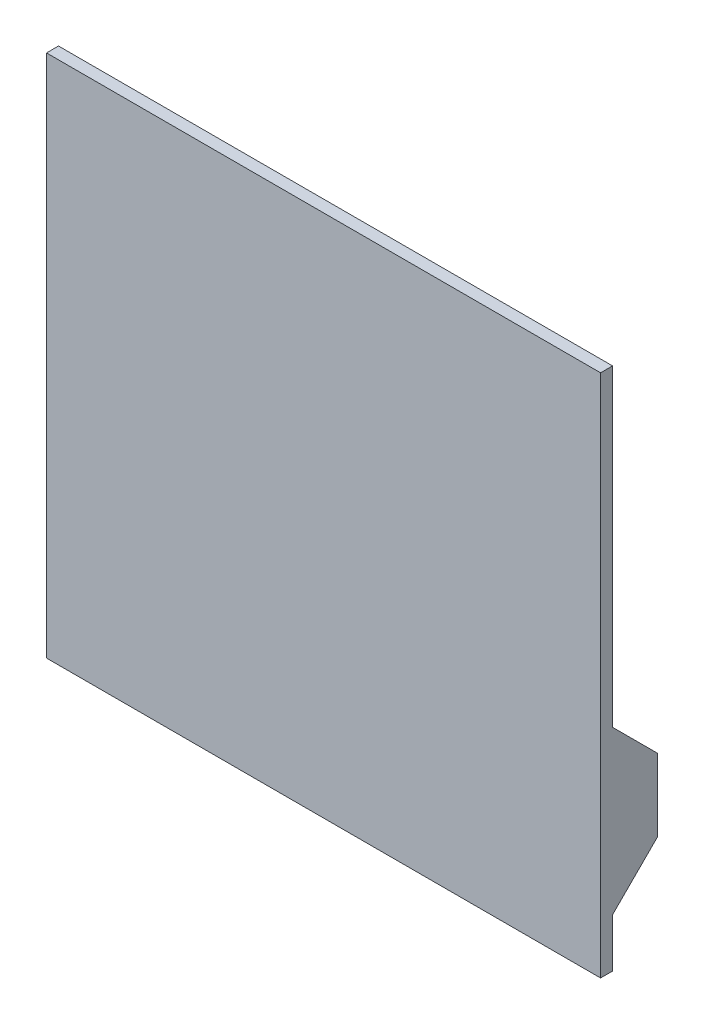
SolidWorks part; units mm, degrees
ref_plane "前基準面" through (0, 0, 0) normal (0, 0, 1) x (1, 0, 0)
ref_plane "上基準面" through (0, 0, 0) normal (0, 1, 0) x (1, 0, 0)
ref_plane "右基準面" through (0, 0, 0) normal (1, 0, 0) x (0, 0, -1)
sketch "草圖1" plane through (0, 0, 0) normal (0, 0, 1) x (1, 0, 0)
  line L1 (-71.1335, 108.4737) -> (113.8665, 108.4737)
  line L2 (-71.1335, 108.4737) -> (-71.1335, -66.5263)
  line L3 (-71.1335, -66.5263) -> (113.8665, -66.5263)
  line L4 (113.8665, 108.4737) -> (113.8665, -66.5263)
  dimension "D1" = 185
  dimension "D2" = 175
extrude "填料-伸長1" add sketch "草圖1" along normal blind 4
sketch "草圖2" plane through (0, 0, 0) normal (0, 0, -1) x (-1, 0, 0)
  line L0 (71.1335, 108.4737) -> (71.1335, -66.5263) construction
  line L1 (71.1335, -60.1263) -> (-68.8665, -60.1263)
  line L2 (71.1335, -60.1263) -> (71.1335, -66.1263)
  line L3 (71.1335, -66.1263) -> (-68.8665, -66.1263)
  line L4 (-68.8665, -60.1263) -> (-68.8665, -66.1263)
  line L5 (-95.4909, -60.0263) -> (-51.1617, -60.0263) construction
  line L6 (71.1335, -50.9263) -> (-68.8665, -50.9263)
  line L7 (71.1335, -50.9263) -> (71.1335, -44.9263)
  line L8 (71.1335, -44.9263) -> (-68.8665, -44.9263)
  line L9 (-68.8665, -50.9263) -> (-68.8665, -44.9263)
  line L10 (-43.7374, -51.0263) -> (-93.6544, -51.0263) construction
  dimension "D1" = 140
  dimension "D2" = 140
  dimension "D3" = 0.1
  dimension "D4" = 6
  dimension "D5" = 0.1
  dimension "D6" = 6
extrude "填料-伸長2" add sketch "草圖2" along normal blind 15
sketch "草圖3" plane through (0, -66.1263, 0) normal (0, -1, 0) x (1, 0, 0)
  line L0 (-65.1335, -10) -> (62.8665, -10) construction
  line L1 (-65.1335, -8.4) -> (62.8665, -8.4)
  line L2 (-65.1335, -11.6) -> (62.8665, -11.6)
  line L3 (68.8665, 0) -> (-71.1335, 0) construction
  line L4 (-71.1335, -15) -> (-71.1335, 0) construction
  line L5 (68.8665, -15) -> (68.8665, 0) construction
  arc A0 (-65.1335, -8.4) -> (-65.1335, -11.6) centre (-65.1335, -10) ccw
  arc A1 (62.8665, -11.6) -> (62.8665, -8.4) centre (62.8665, -10) ccw
  point P2 (-1.1335, -10)
  dimension "D2" = 6
  dimension "D1" = 10
  dimension "D3" = 6
  dimension "D4" = 3.2
extrude "除料-伸長1" cut sketch "草圖3" against normal up to surface (21.2 mm away) up to face at (-1.1335, -44.9263, -7.5)
sketch "草圖4" plane through (0, 0, 0) normal (0, 0, -1) x (-1, 0, 0)
  line L0 (-68.8665, -60.0263) -> (-68.8665, -51.0263)
  line L1 (-68.8665, -60.0263) -> (-113.8665, -60.0263)
  line L2 (-68.8665, -51.0263) -> (-113.8665, -51.0263)
  line L3 (-113.8665, -60.0263) -> (-113.8665, -51.0263)
  line L4 (-68.8665, -69.2263) -> (-113.8665, -69.2263)
  line L5 (-68.8665, -69.2263) -> (-68.8665, -75.2263)
  line L6 (-113.8665, -69.2263) -> (-113.8665, -75.2263)
  line L7 (-68.8665, -75.2263) -> (-113.8665, -75.2263)
  line L8 (-50.0016, -69.1263) -> (-99.9186, -69.1263) construction
  line L10 (-113.8665, -66.5263) -> (-113.8665, 108.4737) construction
  line L20 (71.1335, -60.1263) -> (-68.8665, -60.1263) construction
  line L22 (-68.8665, -50.9263) -> (71.1335, -50.9263) construction
  dimension "D1" = 6
  dimension "D2" = 0.1
  dimension "D3" = 0.1
  dimension "D4" = 0.1
extrude "填料-伸長5" add sketch "草圖4" along normal blind 15
sketch "草圖7" plane through (0, -66.5263, 0) normal (0, -1, 0) x (1, 0, 0)
  line L1 (113.8665, 0) -> (-71.1335, 0)
  line L2 (113.8665, 0) -> (113.8665, 4)
  line L3 (113.8665, 4) -> (-71.1335, 4)
  line L4 (-71.1335, 0) -> (-71.1335, 4)
extrude "填料-伸長6" add sketch "草圖7" along normal blind 40
sketch "草圖6" plane through (0, 108.4737, 0) normal (0, 1, 0) x (1, 0, 0)
  line L1 (113.8665, -4) -> (-71.1335, -4)
  line L2 (113.8665, -4) -> (113.8665, 0)
  line L3 (113.8665, 0) -> (-71.1335, 0)
  line L4 (-71.1335, -4) -> (-71.1335, 0)
extrude "除料-伸長3" cut sketch "草圖6" against normal blind 40
sketch "草圖5" plane through (0, -75.2263, 0) normal (0, -1, 0) x (1, 0, 0)
  line L0 (113.8665, -15) -> (113.8665, 0) construction
  line L1 (113.8665, -15) -> (68.8665, -15) construction
  circle A0 centre (97.3665, -10) radius 1.6
  dimension "D1" = 3.2
  dimension "D2" = 16.5
  dimension "D3" = 5
extrude "除料-伸長2" cut sketch "草圖5" against normal up to surface (24.2 mm away)
sketch "草圖8" plane through (68.8665, 0, 0) normal (1, 0, 0) x (0, 0, -1)
  line L0 (15, -44.9263) -> (15, -75.2263)
  line L1 (15, -75.2263) -> (0, -90.2263)
  line L2 (0, -90.2263) -> (0, -29.9263)
  line L3 (0, -29.9263) -> (15, -44.9263)
  line L4 (15, -44.9263) -> (0, -44.9263) construction
  line L5 (15, -75.2263) -> (0, -75.2263) construction
  dimension "D1" = 45
  dimension "D2" = 45
extrude "填料-伸長7" add sketch "草圖8" along normal blind 3
sketch "草圖9" plane through (113.8665, 0, 0) normal (1, 0, 0) x (0, 0, -1)
  line L0 (15, -51.0263) -> (15, -75.2263)
  line L1 (15, -75.2263) -> (0, -90.2263)
  line L3 (0, -90.2263) -> (0, -36.0263)
  line L4 (0, -36.0263) -> (15, -51.0263)
  point P9 (0, 0)
  dimension "D1" = 45
  dimension "D2" = 45
extrude "填料-伸長8" add sketch "草圖9" against normal blind 4
sketch "草圖11" plane through (-71.1335, 0, 0) normal (-1, 0, 0) x (0, 0, 1)
  line L0 (-15, -66.1263) -> (-15, -44.9263)
  line L1 (-15, -44.9263) -> (0, -29.9263)
  line L2 (0, 68.4737) -> (0, -44.9263) construction
  line L3 (0, -29.9263) -> (0, -81.1263)
  line L4 (0, -66.1263) -> (0, -106.5263) construction
  line L5 (0, -81.1263) -> (-15, -66.1263)
  dimension "D1" = 45
  dimension "D2" = 45
extrude "填料-伸長9" add sketch "草圖11" against normal blind 4
